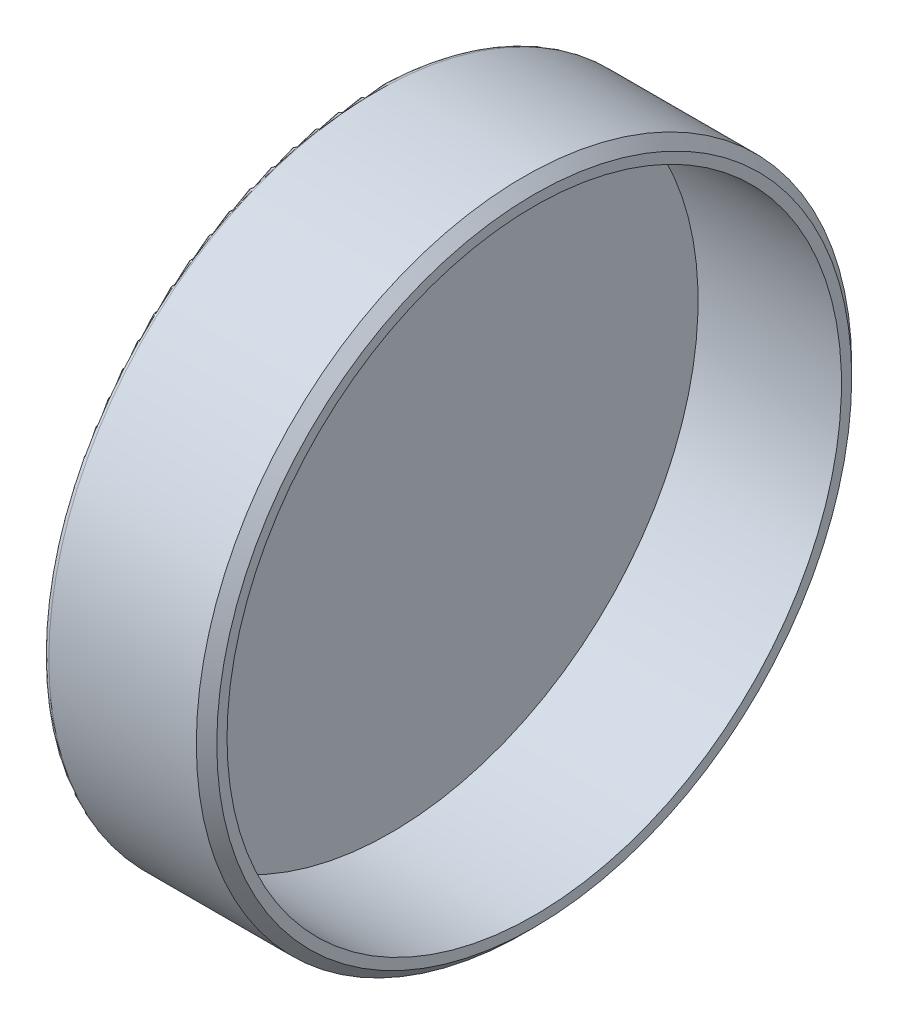
SolidWorks part; units mm, degrees
ref_plane "Plan de face" through (0, 0, 0) normal (0, 0, 1) x (1, 0, 0)
ref_plane "Plan de dessus" through (0, 0, 0) normal (0, 1, 0) x (1, 0, 0)
ref_plane "Plan de droite" through (0, 0, 0) normal (1, 0, 0) x (0, 0, -1)
sketch "Esquisse1" plane through (0, 0, 0) normal (0, 0, 1) x (1, 0, 0)
  line L0 (-7.8927, 0) -> (52.4862, 0) construction
  line L1 (0, 0) -> (0, 16)
  line L2 (0, 16) -> (8, 16)
  dimension "D1" = 32
  dimension "D2" = 8
revolve "Révol.-Mince2" add sketch "Esquisse1" angle 360 about L0
chamfer "Chanfrein1" distance 0.5 angle 45 1 edges at (8, 0, 16)
fillet "Congé1" radius 0.3 1 edges at (0, 0, 16)
